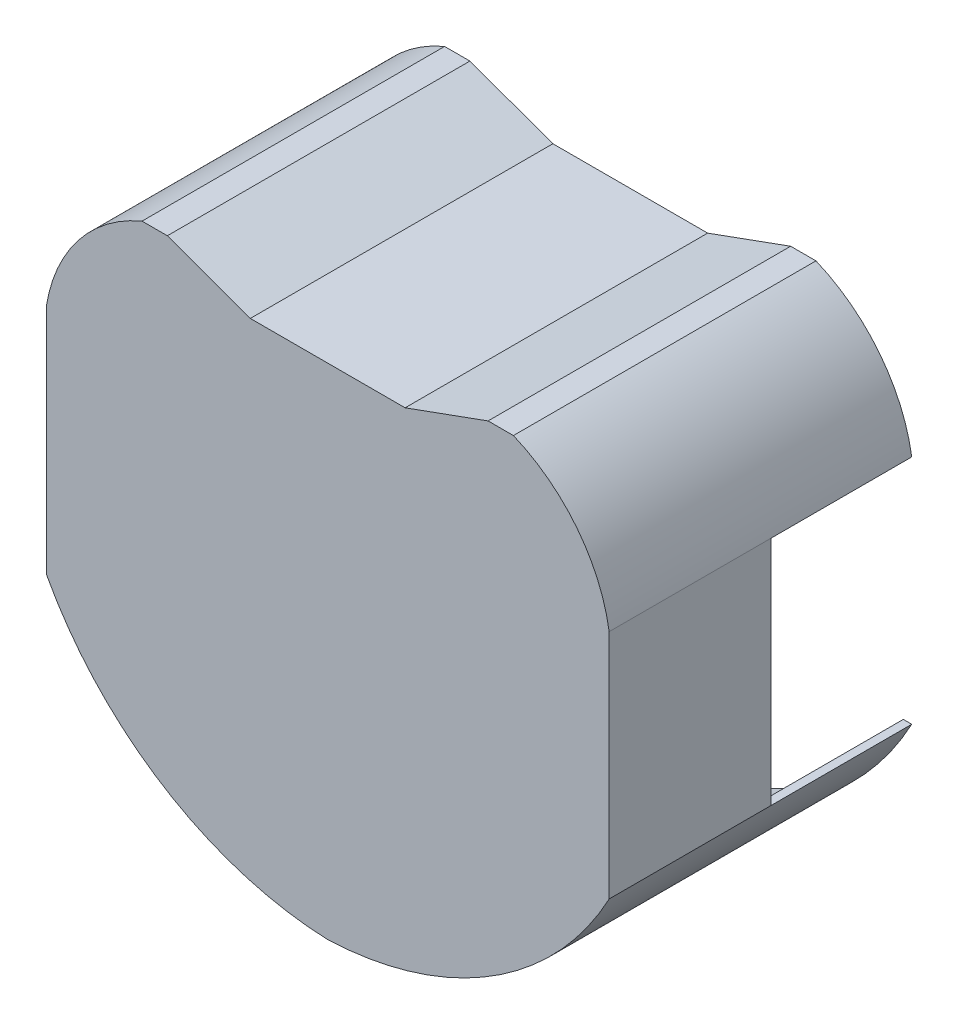
SolidWorks part; units mm, degrees
ref_plane "Front Plane" through (0, 0, 0) normal (0, 0, 1) x (1, 0, 0)
ref_plane "Top Plane" through (0, 0, 0) normal (0, 1, 0) x (1, 0, 0)
ref_plane "Right Plane" through (0, 0, 0) normal (1, 0, 0) x (0, 0, -1)
sketch "Sketch1" plane through (0, 0, 0) normal (0, 0, 1) x (1, 0, 0)
  line L0 (-36.7301, 19.5564) -> (-38.2301, 19.5564) construction
  line L5 (-36.7301, -13.3422) -> (-38.2301, -13.3422) construction
  line L6 (-38.2301, 19.5564) -> (-38.2301, -13.3422)
  line L11 (-25.8205, 32.8873) -> (-25.8205, 34.3873) construction
  line L12 (-22.2205, 32.8873) -> (-22.2205, 34.3873) construction
  line L13 (-10.4304, 28.6071) -> (-10.4304, 30.1071) construction
  line L14 (-25.8205, 34.3873) -> (-22.2205, 34.3873)
  line L15 (-22.2205, 34.3873) -> (-10.4304, 30.1071)
  line L16 (-10.4304, 28.6071) -> (11.5696, 28.6071) construction
  line L17 (0.5696, 28.6071) -> (0.5696, 30.1071) construction
  line L18 (-10.4304, 30.1071) -> (11.5696, 30.1071)
  line L19 (0.5696, -34.3506) -> (0.5696, -35.8506) construction
  line L20 (0.5696, -35.8506) -> (0.5696, -38.3506) construction
  line L21 (-38.2301, -13.3422) -> (-39.4301, -13.3422) construction
  line L22 (-39.4301, -13.3422) -> (-39.4301, 19.5564)
  line L23 (-25.8205, 34.3873) -> (-25.8205, 36.8873) construction
  line L24 (-25.8205, 36.8873) -> (-22.2205, 36.8873)
  line L25 (-10.4304, 30.1071) -> (-10.4304, 32.6071) construction
  line L26 (-22.2205, 36.8873) -> (-10.4304, 32.6071)
  line L27 (-10.4304, 32.6071) -> (11.5696, 32.6071)
  line L28 (11.5696, 30.1071) -> (11.5696, 32.6071) construction
  line L29 (26.9596, 34.3873) -> (26.9596, 36.8873) construction
  line L30 (39.3693, -13.3422) -> (40.5693, -13.3422) construction
  line L31 (11.5696, 28.6071) -> (11.5696, 30.1071) construction
  line L32 (23.3596, 32.8873) -> (23.3596, 34.3873) construction
  line L33 (26.9596, 32.8873) -> (26.9596, 34.3873) construction
  line L34 (37.8693, -13.3422) -> (39.3693, -13.3422) construction
  line L35 (37.8693, 19.5564) -> (39.3693, 19.5564) construction
  line L36 (23.3596, 36.8873) -> (11.5696, 32.6071)
  line L37 (26.9596, 36.8873) -> (23.3596, 36.8873)
  line L38 (40.5693, -13.3422) -> (40.5693, 19.5564)
  line L39 (23.3596, 34.3873) -> (11.5696, 30.1071)
  line L40 (26.9596, 34.3873) -> (23.3596, 34.3873)
  line L41 (39.3693, 19.5564) -> (39.3693, -13.3422)
  arc A0 (-38.2301, 19.5564) -> (-25.8205, 34.3873) centre (-15.4816, 13.1291) cw
  arc A1 (-38.2301, -13.3422) -> (0.5696, -35.8506) centre (0.0239, 7.9043) ccw
  arc A2 (-39.4301, -13.3422) -> (0.5696, -38.3506) centre (2.3999, 9.0699) ccw
  arc A3 (-39.4301, 19.5564) -> (-25.8205, 36.8873) centre (-17.0934, 16.0249) cw
  arc A4 (40.5693, 19.5564) -> (26.9596, 36.8873) centre (18.2325, 16.0249) ccw
  arc A5 (40.5693, -13.3422) -> (0.5696, -38.3506) centre (-1.2607, 9.0699) cw
  arc A6 (39.3693, -13.3422) -> (0.5696, -35.8506) centre (1.1153, 7.9043) cw
  arc A7 (39.3693, 19.5564) -> (26.9596, 34.3873) centre (16.6208, 13.1291) ccw
  point P44 (0.5696, 32.6071)
  dimension "D1" = 1.5
  dimension "D2" = 1.5
  dimension "D3" = 2.5
  dimension "D4" = 1.2
  dimension "D5" = 2.5
  dimension "D6" = 2.5
extrude "Boss-Extrude1" add sketch "Sketch1" along normal blind 20
sketch "Sketch2" plane through (0, 0, 0) normal (0, 0, -1) x (-1, 0, 0)
  line L0 (-40.5693, 19.5564) -> (-39.3693, 19.5564)
  line L1 (-26.9596, 34.3873) -> (-23.3596, 34.3873)
  line L2 (-23.3596, 34.3873) -> (-11.5696, 30.1071)
  line L3 (-11.5696, 30.1071) -> (10.4304, 30.1071)
  line L4 (-26.9596, 36.8873) -> (-23.3596, 36.8873)
  line L5 (-23.3596, 36.8873) -> (-11.5696, 32.6071)
  line L6 (-11.5696, 32.6071) -> (10.4304, 32.6071)
  line L7 (-0.5696, 32.6071) -> (-0.5696, 30.1071)
  line L8 (22.2205, 36.8873) -> (10.4304, 32.6071)
  line L9 (25.8205, 36.8873) -> (22.2205, 36.8873)
  line L10 (22.2205, 34.3873) -> (10.4304, 30.1071)
  line L11 (25.8205, 34.3873) -> (22.2205, 34.3873)
  line L12 (39.4301, 19.5564) -> (38.2301, 19.5564)
  line L13 (-40.5693, -13.3422) -> (-39.3693, -13.3422)
  line L14 (38.2301, -13.3422) -> (39.4301, -13.3422)
  line L15 (-0.5696, -38.3506) -> (-0.5696, -35.8506) construction
  arc A0 (-40.5693, 19.5564) -> (-26.9596, 36.8873) centre (-18.2325, 16.0249) cw
  arc A1 (39.4301, 19.5564) -> (25.8205, 36.8873) centre (17.0934, 16.0249) ccw
  arc A2 (-39.3693, -13.3422) -> (-0.5696, -35.8506) centre (-1.1153, 7.9043) ccw construction
  arc A3 (-40.5693, -13.3422) -> (-0.5696, -38.3506) centre (1.2607, 9.0699) ccw
  arc A4 (-39.3693, -13.3422) -> (-0.5696, -35.8506) centre (-1.1153, 7.9043) ccw
  arc A5 (-0.5696, -38.3506) -> (39.4301, -13.3422) centre (-2.3999, 9.0699) ccw
  arc A6 (-0.5696, -35.8506) -> (38.2301, -13.3422) centre (-0.0239, 7.9043) ccw
  arc A7 (-39.3693, 19.5564) -> (-26.9596, 34.3873) centre (-16.6208, 13.1291) cw
  arc A8 (38.2301, 19.5564) -> (25.8205, 34.3873) centre (15.4816, 13.1291) ccw
  arc M1 (-40.5693, -13.3422) -> (-0.5696, -38.3506) centre (1.2607, 9.0699) ccw
  arc M2 (-0.5696, -38.3506) -> (39.4301, -13.3422) centre (-2.3999, 9.0699) ccw
  arc M4 (39.4301, 19.5564) -> (25.8205, 36.8873) centre (17.0934, 16.0249) ccw
  line M5 (25.8205, 36.8873) -> (22.2205, 36.8873)
  line M6 (22.2205, 36.8873) -> (10.4304, 32.6071)
  line M7 (10.4304, 32.6071) -> (-11.5696, 32.6071)
  line M8 (-11.5696, 32.6071) -> (-23.3596, 36.8873)
  line M9 (-23.3596, 36.8873) -> (-26.9596, 36.8873)
  arc M10 (-26.9596, 36.8873) -> (-40.5693, 19.5564) centre (-18.2325, 16.0249) ccw
  line M12 (22.2205, 34.3873) -> (25.8205, 34.3873)
  arc M13 (25.8205, 34.3873) -> (38.2301, 19.5564) centre (15.4816, 13.1291) cw
  arc M15 (38.2301, -13.3422) -> (-0.5696, -35.8506) centre (-0.0239, 7.9043) cw
  arc M16 (-0.5696, -35.8506) -> (-39.3693, -13.3422) centre (-1.1153, 7.9043) cw
  arc M18 (-39.3693, 19.5564) -> (-26.9596, 34.3873) centre (-16.6208, 13.1291) cw
  line M19 (-26.9596, 34.3873) -> (-23.3596, 34.3873)
  line M20 (-23.3596, 34.3873) -> (-11.5696, 30.1071)
  line M21 (-11.5696, 30.1071) -> (10.4304, 30.1071)
  line M22 (10.4304, 30.1071) -> (22.2205, 34.3873)
extrude "Boss-Extrude2" add sketch "Sketch2" along normal blind 20 contours L7 L6 L0 M8 M9 M10 M18 M19 M20 M21 | L12 L7 L3 M4 M5 M6 M7 M22 M12 M13 | L15 L13 M1 M16 | L15 L14 M2 M15
sketch "Sketch3" plane through (0, 0, 20) normal (0, 0, 1) x (1, 0, 0)
  line L0 (-25.8205, 36.8873) -> (-22.2205, 36.8873)
  line L1 (-22.2205, 36.8873) -> (-10.4304, 32.6071)
  line L2 (-10.4304, 32.6071) -> (11.5696, 32.6071)
  line L3 (11.5696, 32.6071) -> (23.3596, 36.8873)
  line L4 (23.3596, 36.8873) -> (26.9596, 36.8873)
  line L5 (40.5693, 19.5564) -> (40.5693, -13.3422)
  line L6 (-39.4301, -13.3422) -> (-39.4301, 19.5564)
  arc A0 (-39.4301, -13.3422) -> (0.5696, -38.3506) centre (2.3999, 9.0699) ccw
  arc A1 (0.5696, -38.3506) -> (40.5693, -13.3422) centre (-1.2607, 9.0699) ccw
  arc A2 (-39.4301, 19.5564) -> (-25.8205, 36.8873) centre (-17.0934, 16.0249) cw
  arc A3 (26.9596, 36.8873) -> (40.5693, 19.5564) centre (18.2325, 16.0249) cw
extrude "Boss-Extrude3" add sketch "Sketch3" along normal blind 3
